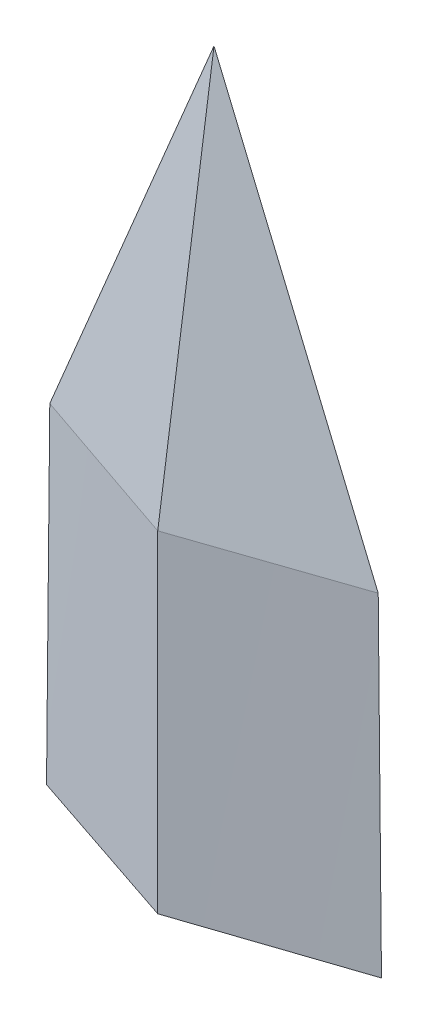
SolidWorks part; units mm, degrees
ref_plane "Front Plane" through (0, 0, 0) normal (0, 0, 1) x (1, 0, 0)
ref_plane "Top Plane" through (0, 0, 0) normal (0, 1, 0) x (1, 0, 0)
ref_plane "Right Plane" through (0, 0, 0) normal (1, 0, 0) x (0, 0, -1)
sketch "Sketch1" plane through (0, 0, 0) normal (0, 0, 1) x (1, 0, 0)
  line L0 (142.4212, 465.168) -> (219.716, 465.168)
  line L1 (219.716, 465.168) -> (213.5025, 1096.9676)
  line L2 (213.5025, 1096.9676) -> (181.0686, 1174.3372)
  line L3 (181.0686, 1174.3372) -> (148.6348, 1096.9676)
  line L4 (148.6348, 1096.9676) -> (142.4212, 465.168)
  point P2 (181.0686, 465.168)
extrude "Boss-Extrude1" add sketch "Sketch1" along normal blind 11.1125 and the other way blind 11.1125
sketch "Sketch2" plane through (0, 465.168, 0) normal (0, -1, 0) x (1, 0, 0)
  line L0 (142.4212, 0) -> (181.0686, 11.1125)
  line L1 (142.4212, -11.1125) -> (142.4212, 11.1125) construction
  line L2 (142.4212, 11.1125) -> (219.716, 11.1125) construction
  line L3 (181.0686, 11.1125) -> (219.716, 0)
  line L4 (219.716, -11.1125) -> (219.716, 11.1125) construction
  line L8 (142.4212, 0) -> (137.8486, 0)
  line L9 (137.8486, 0) -> (137.8486, 15.2584)
  line L10 (137.8486, 15.2584) -> (222.7051, 15.2584)
  line L11 (222.7051, 15.2584) -> (222.7051, 0)
  line L12 (222.7051, 0) -> (219.716, 0)
ref_plane "Plane1" through (0, 1096.9676, 0) normal (0, 1, 0) x (1, 0, 0)
sketch "Sketch3" plane through (0, 1096.9676, 0) normal (0, 1, 0) x (1, 0, 0)
  line L1 (148.6348, 11.1125) -> (148.6348, -11.1125) construction
  line L3 (213.5025, 11.1125) -> (213.5025, -11.1125) construction
  line L4 (213.5025, 0) -> (181.0686, -11.1125)
  line L5 (181.0686, -11.1125) -> (148.6348, 0)
  line L6 (148.6348, 0) -> (137.8486, 0)
  line L7 (137.8486, 0) -> (137.8486, -15.2584)
  line L8 (137.8486, -15.2584) -> (222.7051, -15.2584)
  line L9 (222.7051, -15.2584) -> (222.7051, 0)
  line L10 (222.7051, 0) -> (213.5025, 0)
loft "Cut-Loft1" cut profiles "Sketch2", "Sketch3"
mirror "Mirror1" about plane through (0, 0, 0) normal (0, 0, 1) of "Cut-Loft1"
ref_plane "Plane2" through (-32.1031, 13.4578, 93.6987) normal (-0.3212, 0.1346, 0.9374) x (0.947, 0.0457, 0.3179)
sketch "Sketch5" plane through (-32.1031, 13.4578, 93.6987) normal (-0.3212, 0.1346, 0.9374) x (0.947, 0.0457, 0.3179)
  line L1 (164.4105, 1280.8293) -> (274.288, 1280.8293)
  line L2 (164.4105, 1280.8293) -> (164.4105, 997.7782)
  line L3 (164.4105, 997.7782) -> (274.288, 997.7782)
  line L4 (274.288, 1280.8293) -> (274.288, 997.7782)
extrude "Cut-Extrude2" cut sketch "Sketch5" along normal through all
ref_plane "Plane3" through (69.4583, 29.1174, 202.7265) normal (0.3212, 0.1346, 0.9374) x (0.947, -0.0457, -0.3179)
sketch "Sketch6" plane through (69.4583, 29.1174, 202.7265) normal (0.3212, 0.1346, 0.9374) x (0.947, -0.0457, -0.3179)
  line L1 (57.1921, 1173.3831) -> (206.3136, 1173.3831)
  line L2 (57.1921, 1173.3831) -> (57.1921, 1064.4614)
  line L3 (57.1921, 1064.4614) -> (206.3136, 1064.4614)
  line L4 (206.3136, 1173.3831) -> (206.3136, 1064.4614)
extrude "Cut-Extrude3" cut sketch "Sketch6" along normal through all
mirror "Mirror2" about plane through (0, 0, 0) normal (0, 0, 1) of "Cut-Extrude2", "Cut-Extrude3"
sketch "Sketch7" plane through (0, 465.168, 0) normal (0, -1, 0) x (1, 0, 0)
  circle A0 centre (181.0686, 0) radius 4.7625
  dimension "D1" = 9.525
extrude "Cut-Extrude4" cut sketch "Sketch7" against normal blind 635
sketch "Sketch8" plane through (0, 0, 0) normal (0, 0, 1) x (1, 0, 0)
  line L0 (105.7103, 602.8372) -> (255.485, 602.8372)
  line L1 (105.7103, 1207.5881) -> (255.485, 1207.5881)
  line L2 (105.7103, 1207.5881) -> (105.7103, 454.0044)
  line L3 (105.7103, 454.0044) -> (255.485, 454.0044)
  line L4 (255.485, 1207.5881) -> (255.485, 454.0044)
  line L5 (255.485, 745.7122) -> (105.7103, 745.7122)
  line L6 (105.7103, 888.5872) -> (255.485, 888.5872)
  line L7 (255.485, 1031.4622) -> (105.7103, 1031.4622)
  dimension "D1" = 142.875
  dimension "D2" = 142.875
  dimension "D3" = 142.875
  dimension "D4" = 142.875
extrude "Cut-Extrude8" cut sketch "Sketch8" against normal through all and the other way through all contours L4 L0 L2 L3 | L4 L5 L2 L0 | L6 L2 L5 L4 | L4 L7 L2 L6
sketch "Sketch17" plane through (0, 1031.4622, 0) normal (0, -1, 0) x (1, 0, 0)
  circle A0 centre (168.3686, 0) radius 1.5875
  circle A1 centre (193.7686, 0) radius 1.5875
  circle A2 centre (181.0686, 0) radius 4.7625 construction
  circle A3 centre (181.0686, 0) radius 4.7625 construction
  dimension "D1" = 12.7
  dimension "D2" = 12.7
  dimension "D3" = 3.175
extrude "Cut-Extrude15" cut sketch "Sketch17" against normal blind 12.7
